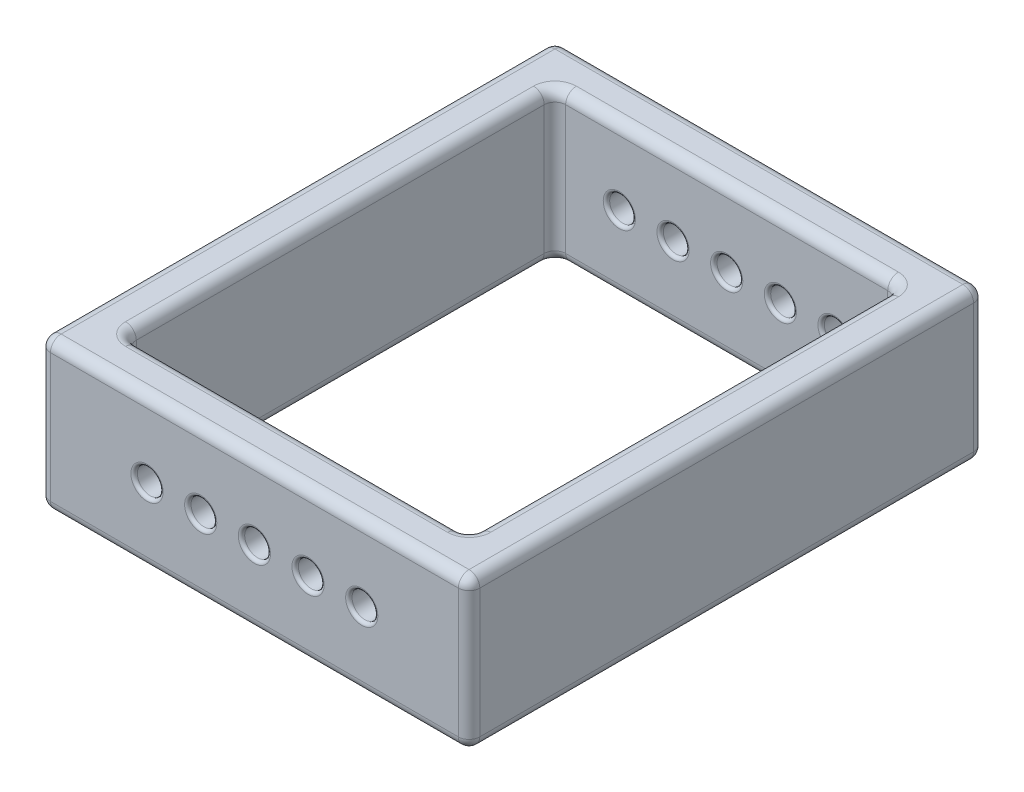
SolidWorks part; units mm, degrees
ref_plane "Front Plane" through (0, 0, 0) normal (0, 0, 1) x (1, 0, 0)
ref_plane "Top Plane" through (0, 0, 0) normal (0, 1, 0) x (1, 0, 0)
ref_plane "Right Plane" through (0, 0, 0) normal (1, 0, 0) x (0, 0, -1)
sketch "Sketch1" plane through (0, 0, 0) normal (0, 0, 1) x (1, 0, 0)
  line L1 (-20, 7) -> (20, 7)
  line L2 (-20, 7) -> (-20, -7)
  line L3 (-20, -7) -> (20, -7)
  line L4 (20, 7) -> (20, -7)
  dimension "D1" = 40
  dimension "D2" = 14
  dimension "D3" = 7
  dimension "D4" = 20
extrude "Boss-Extrude1" add sketch "Sketch1" along normal blind 48
sketch "Sketch3" plane through (0, 7, 0) normal (0, 1, 0) x (1, 0, 0)
  line L0 (20, 0) -> (-20, 0) construction
  line L1 (-16, -4) -> (16, -4)
  line L2 (-16, -4) -> (-16, -44)
  line L3 (-16, -44) -> (16, -44)
  line L4 (16, -4) -> (16, -44)
  line L5 (-20, -48) -> (-20, 0) construction
  line L6 (20, -48) -> (-20, -48) construction
  line L7 (20, -48) -> (20, 0) construction
  dimension "D1" = 4
  dimension "D2" = 4
  dimension "D3" = 4
  dimension "D4" = 4
extrude "Cut-Extrude1" cut sketch "Sketch3" against normal blind 48
sketch "Sketch4" plane through (0, 0, 48) normal (0, 0, 1) x (1, 0, 0)
  line L0 (-20, -7) -> (20, -7) construction
  point P0 (-10, 0)
  point P2 (-5, 0)
  point P4 (0, 0)
  point P6 (5, 0)
  point P8 (10, 0)
  dimension "D1" = 5
  dimension "D2" = 0
  dimension "D3" = 10
  dimension "D4" = 5
  dimension "D5" = 10
  dimension "D6" = 7
  dimension "D7" = 7
  dimension "D8" = 7
  dimension "D9" = 7
  dimension "D10" = 7
hole_wizard "Ø2.4 (2.4) Diameter Hole1" positions "Sketch4" profile "Sketch5" hole size "Ø2.4" standard "ANSI Metric" end condition through all
sketch "Sketch5" plane through (-10, 0, 48) normal (1, 0, 0) x (0, -1, 0)
  line L0 (0, 0) -> (0, 48)
  line L1 (0, 48) -> (1.2, 48)
  line L2 (1.2, 48) -> (1.2, 0)
  line L5 (1.2, 0) -> (0, 0)
  line L11 (0, -6.35) -> (0, 107.95) construction
  dimension "Thru Hole Dia." = 2.4
  dimension "Thru Hole Depth" = 48
fillet "Fillet1" radius 1 24 edges at (20, -7, 24) (0, -7, 0) (20, 0, 0) (16, 0, 44) (16, -7, 24) (0, -7, 44) (-16, 0, 44) (-16, -7, 24) (-16, 0, 4) (0, -7, 4) (0, 7, 0) (16, 0, 4) (16, 7, 24) (20, 7, 24) (20, 0, 48) (0, -7, 48) (-20, 0, 48) (-20, 0, 0) (-20, -7, 24) (-20, 7, 24) (0, 7, 4) (-16, 7, 24) (0, 7, 44) (0, 7, 48)
fillet "Fillet2" radius 0.3 20 edges at (11.2, 0, 0) (6.2, 0, 0) (1.2, 0, 0) (-3.8, 0, 0) (-8.8, 0, 0) (11.2, 0, 44) (6.2, 0, 44) (1.2, 0, 44) (-3.8, 0, 44) (-8.8, 0, 44) (8.8, 0, 4) (3.8, 0, 4) (-1.2, 0, 4) (-6.2, 0, 4) (-11.2, 0, 4) (11.2, 0, 48) (6.2, 0, 48) (1.2, 0, 48) (-3.8, 0, 48) (-8.8, 0, 48)
